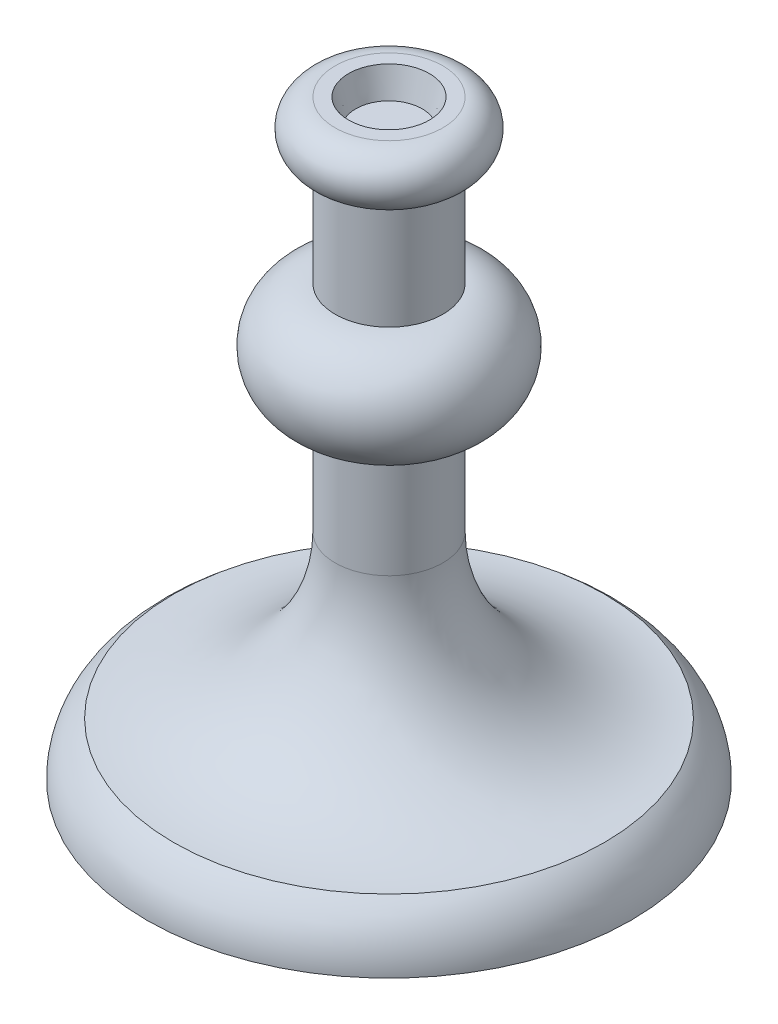
SolidWorks part; units mm, degrees
ref_plane "Front Plane" through (0, 0, 0) normal (0, 0, 1) x (1, 0, 0)
ref_plane "Top Plane" through (0, 0, 0) normal (0, 1, 0) x (1, 0, 0)
ref_plane "Right Plane" through (0, 0, 0) normal (1, 0, 0) x (0, 0, -1)
sketch "Sketch1" plane through (0, 0, 0) normal (0, 0, 1) x (1, 0, 0)
  line L0 (0, 0) -> (0, 220)
  line L1 (0, 220) -> (20, 220)
  line L2 (20, 200) -> (20, 160)
  line L3 (20, 120) -> (20, 80)
  line L4 (0, 0) -> (90, 0)
  arc A0 (20, 220) -> (20, 200) centre (20, 210) cw
  arc A1 (20, 160) -> (20, 120) centre (20, 140) cw
  arc A2 (20, 80) -> (80, 20) centre (80, 80) ccw
  arc A4 (90, 0) -> (80, 20) centre (65, 0) ccw
  dimension "D3" = 10
  dimension "D5" = 20
  dimension "D7" = 60
  dimension "D1" = 220
  dimension "D2" = 20
  dimension "D4" = 40
  dimension "D6" = 40
  dimension "D8" = 90
revolve "Revolve1" add sketch "Sketch1" angle 360 about L0
sketch "Sketch3" plane through (0, 220, 0) normal (0, 1, 0) x (1, 0, 0)
  circle A0 centre (0, 0) radius 15
  dimension "D1" = 30
extrude "Cut-Extrude1" cut sketch "Sketch3" against normal blind 10 draft 15
